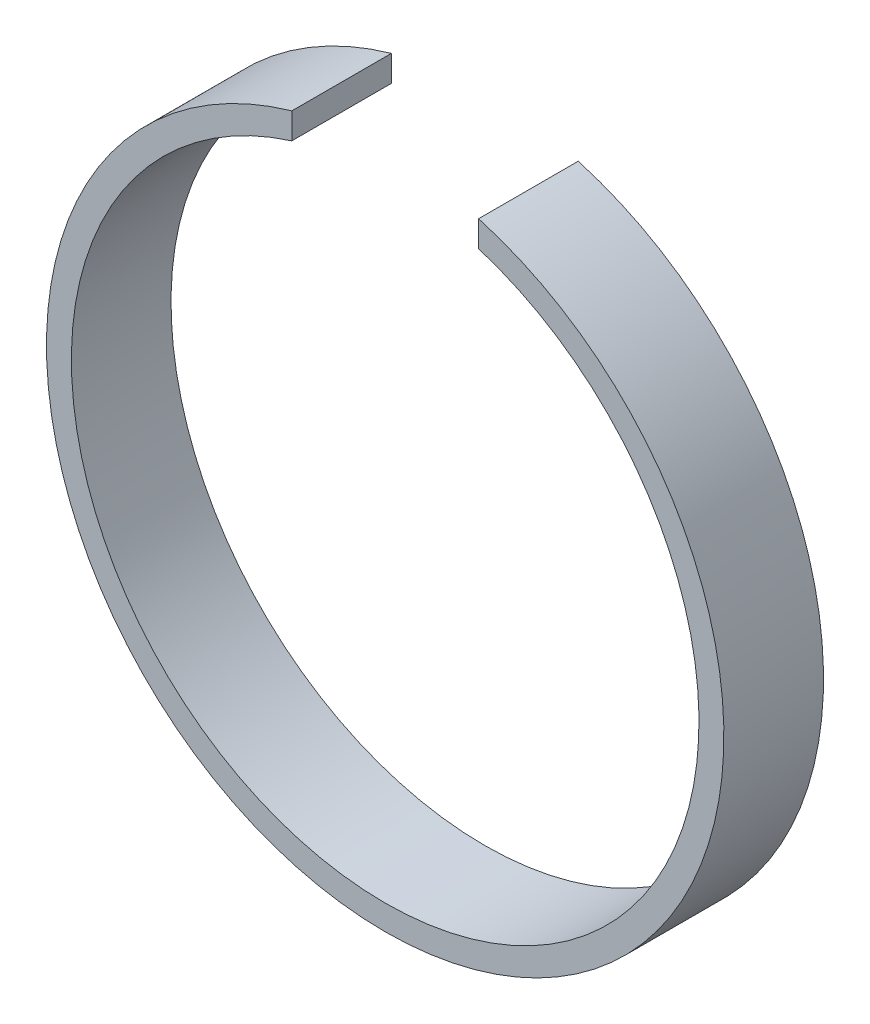
SolidWorks part; units mm, degrees
ref_plane "Front Plane" through (0, 0, 0) normal (0, 0, 1) x (1, 0, 0)
ref_plane "Top Plane" through (0, 0, 0) normal (0, 1, 0) x (1, 0, 0)
ref_plane "Right Plane" through (0, 0, 0) normal (1, 0, 0) x (0, 0, -1)
sketch "Sketch1" plane through (0, 0, 0) normal (0, 0, 1) x (1, 0, 0)
  line L3 (-100.5, 26.1456) -> (-100.5, 24.0581)
  line L6 (-85.5, 26.1456) -> (-85.5, 24.0581)
  arc A1 (-100.5, 24.0581) -> (-85.5, 24.0581) centre (-93, 0) ccw
  arc A3 (-100.5, 26.1456) -> (-85.5, 26.1456) centre (-93, 0) ccw
  circle A5 centre (-93, 0) radius 25.2 construction
  circle A6 centre (-93, 0) radius 27.2 construction
  point P3 (-93, 26.6004)
  point P5 (-93, 26.6004)
extrude "Boss-Extrude1" add sketch "Sketch1" along normal blind 8
